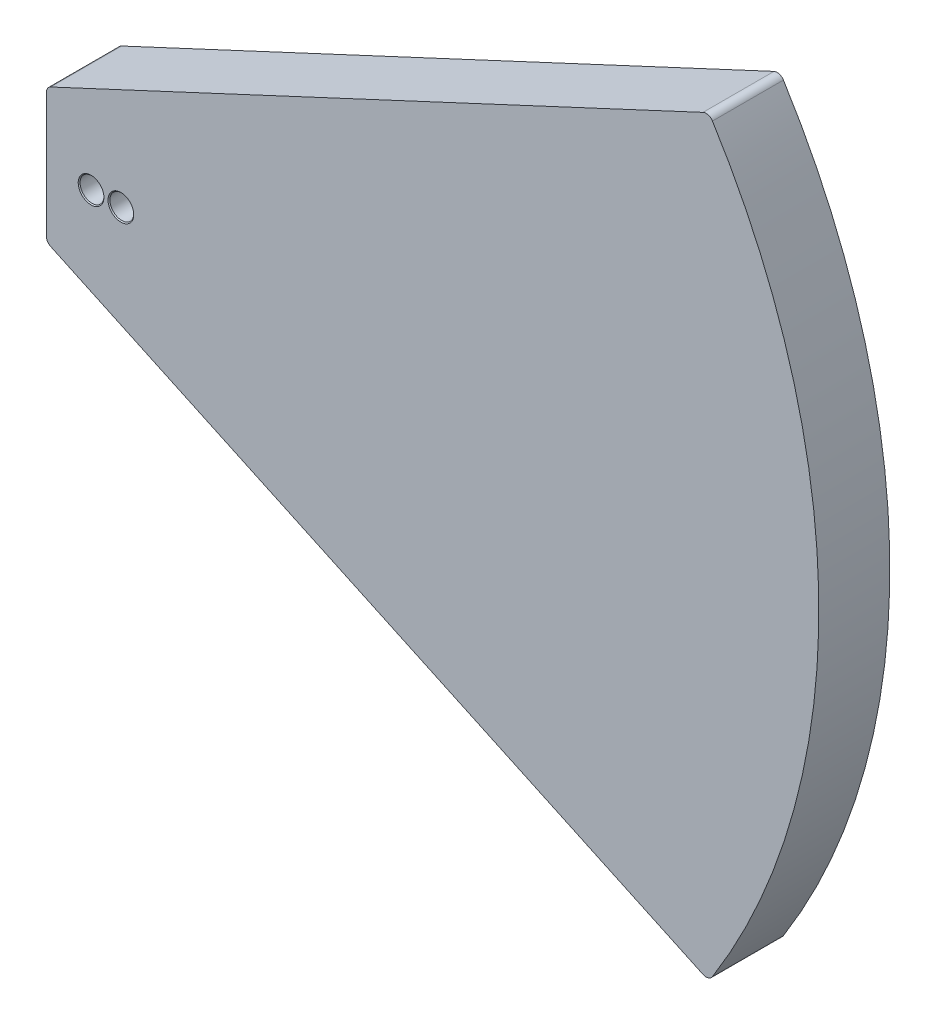
SolidWorks part; units mm, degrees
ref_plane "Front Plane" through (0, 0, 0) normal (1, 0, 0) x (0, 1, 0)
ref_plane "Top Plane" through (0, 0, 0) normal (0, 0, 1) x (0, 1, 0)
ref_plane "Right Plane" through (0, 0, 0) normal (0, 1, 0) x (-1, 0, 0)
sketch "Sketch1" plane through (0, 0, 0) normal (0, 0, 1) x (0, 1, 0)
  line L1 (-4, 0) -> (-4, 10)
  line L2 (-4, 10) -> (4, 10)
  line L3 (4, 10) -> (4, 0)
  line L4 (0, 0) -> (0, 4) construction
  arc A0 (-4, 0) -> (4, 0) centre (0, 0) ccw
  circle A1 centre (0, 0) radius 1.5 construction
  circle A2 centre (0, 4) radius 1.5 construction
  dimension "D1" = 4
  dimension "D4" = 3
  dimension "D2" = 10
  dimension "D3" = 4
sketch "Sketch2" plane through (0, 0, 0) normal (0, 0, 1) x (0, 1, 0)
  line L0 (-9, 10) -> (9, 10)
  line L1 (9, 10) -> (50.4548, -78.9)
  line L2 (-9, 10) -> (-50.4548, -78.9)
  line L3 (-4, 0) -> (-4, 10) construction
  line L4 (-50.4548, -78.9) -> (50.4548, -78.9) construction
  arc A0 (-50.4548, -78.9) -> (50.4548, -78.9) centre (0, 0) ccw
  point P6 (34.3852, -57.0782)
  point P10 (0, 0)
  point P11 (46.3472, -43.1552)
  point P12 (25.1685, -53.5)
  point P14 (32.4242, -53.5)
  dimension "D1" = 5
  dimension "D2" = 5
  dimension "D3" = 88.9
  dimension "D4" = 50
extrude "Boss-Extrude1" add sketch "Sketch2" along normal blind 9.525
sketch "Sketch3" plane through (0, 0, 0) normal (0, 0, -1) x (1, 0, 0)
  line L2 (-10, -4.5) -> (-10, 4.5)
  line L4 (-10, -4.5) -> (0, -4.5)
  line L5 (0, 4.5) -> (-10, 4.5)
  line L6 (-10, -4.5) -> (0, -4.5)
  line L7 (0, 4.5) -> (-10, 4.5)
  arc A2 (0, -4.5) -> (0, 4.5) centre (0, 0) ccw
  arc A3 (0, -4.5) -> (0, 4.5) centre (0, 0) ccw
  dimension "D1" = 0.5
extrude "Cut-Extrude2" cut sketch "Sketch3" against normal blind 4
hole_wizard "M3 Clearance Hole1" positions "Sketch4" profile "Sketch5" hole size "M3" standard "ANSI Metric" end condition through all
sketch "Sketch4" plane through (0, 0, 9.525) normal (0, 0, 1) x (0, -1, 0)
  point P0 (0, 0)
  point P3 (0, -4)
sketch "Sketch5" plane through (0, 0, 9.525) normal (1, 0, 0) x (0, -1, 0)
  line L0 (0, 0) -> (0, 9.525)
  line L1 (0, 9.525) -> (1.6, 9.525)
  line L2 (1.6, 9.525) -> (1.6, 0.125)
  line L3 (1.6, 0.125) -> (1.725, 0)
  line L5 (1.725, 0) -> (0, 0)
  line L6 (-1.6, 0.125) -> (-1.725, 0) construction
  line L11 (0, -6.35) -> (0, 107.95) construction
  dimension "Thru Hole Dia." = 3.2
  dimension "Thru Hole Depth" = 9.525
  dimension "Near C'Sink Dia." = 3.45
  dimension "Near C'Sink Angle" = 90
fillet "Fillet1" radius 1 6 edges at (-10, -4.5, 2) (-10, -9, 4.7625) (78.9, 50.4548, 4.7625) (-10, 9, 4.7625) (-10, 4.5, 2) (78.9, -50.4548, 4.7625)
